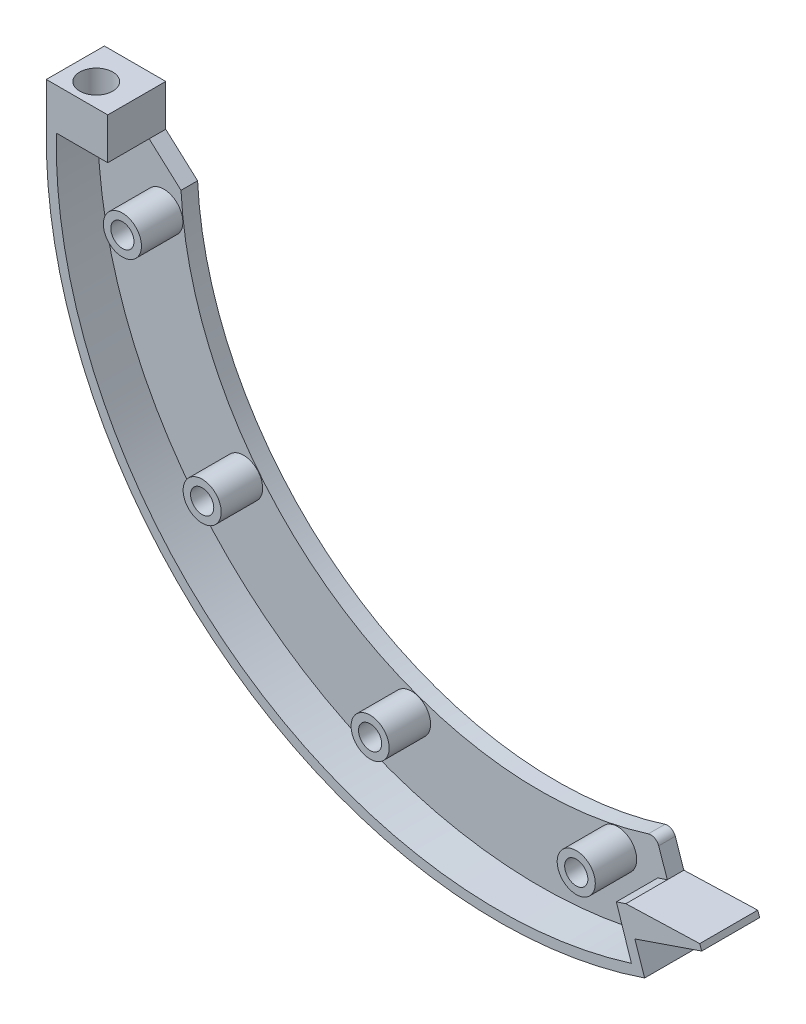
SolidWorks part; units mm, degrees
ref_plane "前视基准面" through (0, 0, 0) normal (0, 0, 1) x (1, 0, 0)
ref_plane "上视基准面" through (0, 0, 0) normal (0, 1, 0) x (1, 0, 0)
ref_plane "右视基准面" through (0, 0, 0) normal (1, 0, 0) x (0, 0, -1)
sketch "Sketch1" plane through (0, 0, 0) normal (0, 0, 1) x (1, 0, 0)
  line L2 (16.8879, -133.3693) -> (14.6737, -134.1273)
  line L3 (14.6737, -134.1273) -> (15.8677, -137.6154)
  line L5 (-48.9405, -84.8) -> (-45.0968, -88.2603)
  line L7 (-48.9405, -84.8) -> (-56.3425, -84.8)
  line L8 (12.5607, -127.9544) -> (13.5977, -130.9838)
  line L10 (16.8879, -133.3693) -> (22.7495, -131.3629)
  line L11 (22.5089, -130.6992) -> (22.7495, -131.3629)
  line L12 (13.5977, -130.9838) -> (22.5089, -130.6992)
  arc A0 (12.5607, -127.9544) -> (11.3122, -127.3251) centre (11.6146, -128.2783) ccw
  arc A6 (-56.3425, -84.8) -> (15.8677, -137.6154) centre (-1.8002, -86) ccw
  arc A9 (-45.0968, -88.2603) -> (11.3122, -127.3251) centre (-1.8002, -86) ccw
  dimension "D1" = 1
extrude "Boss-Extrude1" add sketch "Sketch1" along normal blind 2
sketch "Sketch2" plane through (0, 0, 2) normal (0, 0, 1) x (1, 0, 0)
  line L1 (-56.3425, -84.8) -> (-55.1422, -84.8)
  line L6 (22.5089, -130.6992) -> (13.5977, -130.9838)
  line L7 (-48.9405, -84.8) -> (-56.3425, -84.8)
  line L10 (14.2618, -136.8805) -> (12.45, -131.3605)
  line L11 (15.8677, -137.6154) -> (13.5977, -130.9838)
  line L12 (13.5977, -130.9838) -> (12.45, -131.3605)
  line L14 (-45.0968, -88.2603) -> (-48.9405, -84.8)
  line L18 (22.7495, -131.3629) -> (22.5089, -130.6992)
  line L23 (13.5977, -130.9838) -> (12.5607, -127.9544)
  line L25 (15.8677, -137.6154) -> (14.6737, -134.1273)
  line L27 (14.6737, -134.1273) -> (22.7495, -131.3629)
  arc A0 (-56.3557, -86) -> (-56.3425, -84.8) centre (-1.8002, -86) cw
  arc A1 (-55.1557, -86) -> (-55.1422, -84.8) centre (-1.8002, -86) cw
  arc A2 (15.2133, -137.8348) -> (15.8677, -137.6154) centre (-1.8002, -86) ccw
  arc A3 (12.5607, -127.9544) -> (11.3122, -127.3251) centre (11.6146, -128.2783) ccw
  arc A4 (-55.1557, -86) -> (14.2618, -136.8805) centre (-1.8002, -86) ccw
  arc A6 (-56.3425, -84.8) -> (15.8677, -137.6154) centre (-1.8002, -86) ccw
  arc A7 (-45.0968, -88.2603) -> (11.3122, -127.3251) centre (-1.8002, -86) ccw
  arc A8 (-56.3557, -86) -> (15.2133, -137.8348) centre (-1.8002, -86) ccw
  dimension "D1" = 0
extrude "Boss-Extrude2" add sketch "Sketch2" along normal blind 5
sketch "Sketch3" plane through (0, 0, 2) normal (0, 0, 1) x (1, 0, 0)
  line L0 (-1.8002, -86) -> (12.1201, -152.1768) construction
  line L1 (14.6737, -134.1273) -> (22.7495, -131.3629) construction
  line L4 (22.7495, -131.3629) -> (22.5089, -130.6992) construction
  line L5 (22.5089, -130.6992) -> (13.5977, -130.9838) construction
  line L6 (14.6737, -134.1273) -> (22.7495, -131.3629)
  line L7 (22.7495, -131.3629) -> (22.5089, -130.6992)
  line L8 (22.5089, -130.6992) -> (13.5977, -130.9838)
  line L9 (13.5977, -130.9838) -> (14.6737, -134.1273)
  circle A2 centre (7.6073, -130.7228) radius 2.3
  circle A3 centre (-17.2718, -129.003) radius 2.3
  circle A4 centre (-37.5439, -114.4784) radius 2.3
  circle A5 centre (-47.1727, -91.4738) radius 2.3
  point P13 (-1.8002, -86)
  dimension "D1" = 4.6
  dimension "D2" = 4
extrude "Boss-Extrude3" add sketch "Sketch3" along normal blind 5
sketch "Sketch4" plane through (0, -84.8, 0) normal (0, 1, 0) x (1, 0, 0)
  line L0 (-56.3425, -7) -> (-56.3425, 0) construction
  line L1 (-56.3425, 0) -> (-48.9405, 0)
  line L2 (-56.3425, 0) -> (-56.3557, -7)
  line L3 (-56.3557, -7) -> (-48.9405, -7)
  line L4 (-48.9405, 0) -> (-48.9405, -7)
  line L5 (-48.9405, 0) -> (-56.3425, 0) construction
  line L6 (-55.1557, -7) -> (-56.3557, -7) construction
  line L7 (-55.1557, -7) -> (-56.3557, -7) construction
extrude "Boss-Extrude4" add sketch "Sketch4" along normal blind 5
sketch "Sketch6" plane through (0, 0, 7) normal (0, 0, 1) x (1, 0, 0)
  circle A0 centre (-47.1727, -91.4738) radius 1.4
  circle A1 centre (-37.5439, -114.4784) radius 1.4
  circle A2 centre (-17.2718, -129.003) radius 1.4
  circle A3 centre (7.6073, -130.7228) radius 1.4
extrude "Cut-Extrude1" cut sketch "Sketch6" against normal blind 5
sketch "Sketch7" plane through (0, -79.8, 0) normal (0, 1, 0) x (1, 0, 0)
  circle A1 centre (-53.1133, -4.2128) radius 2
extrude "Cut-Extrude2" cut sketch "Sketch7" against normal blind 8
